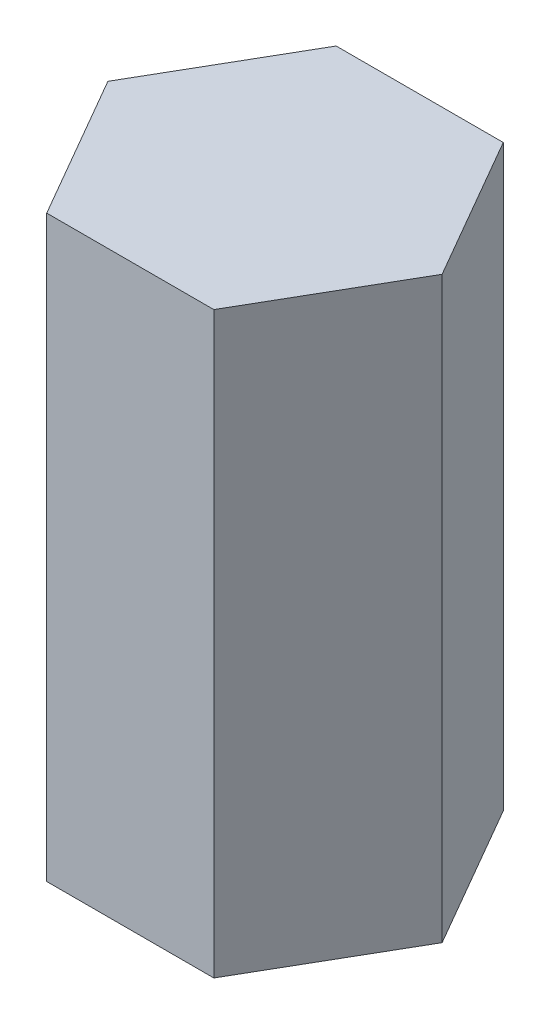
SolidWorks part; units mm, degrees
material "보통 탄소강"
ref_plane "Front" through (0, 0, 0) normal (0, 0, 1) x (1, 0, 0)
ref_plane "Top" through (0, 0, 0) normal (0, 1, 0) x (1, 0, 0)
ref_plane "Right" through (0, 0, 0) normal (1, 0, 0) x (0, 0, -1)
sketch "Sketch1" plane through (0, 0, 0) normal (0, 1, 0) x (1, 0, 0)
  line L1 (-7.2169, 12.5) -> (-14.4338, 0)
  line L2 (-14.4338, 0) -> (-7.2169, -12.5)
  line L3 (-7.2169, -12.5) -> (7.2169, -12.5)
  line L4 (7.2169, -12.5) -> (14.4338, 0)
  line L5 (14.4338, 0) -> (7.2169, 12.5)
  line L6 (7.2169, 12.5) -> (-7.2169, 12.5)
  circle A0 centre (0, 0) radius 12.5 construction
  dimension "D1" = 25
extrude "Extrude1" add sketch "Sketch1" along normal blind 50
equation "\"D\" = 25mm"
equation "\"H\" = 50mm"
equation "\"D1@Sketch1\"= \"D\""
equation "\"D1@Extrude1\"= \"H\""
